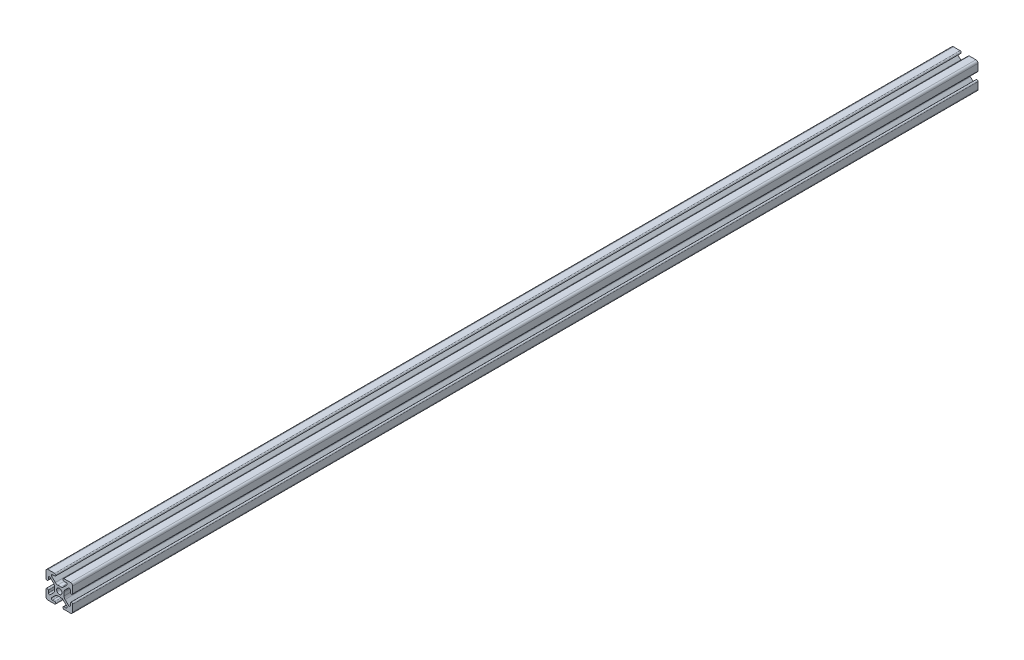
SolidWorks part; units mm, degrees
ref_plane "Front Plane" through (0, 0, 0) normal (0, 0, 1) x (1, 0, 0)
ref_plane "Top Plane" through (0, 0, 0) normal (0, 1, 0) x (1, 0, 0)
ref_plane "Right Plane" through (0, 0, 0) normal (1, 0, 0) x (0, 0, -1)
ref_plane "Plane1" through (0, 0, -25) normal (0, 0, -1) x (-1, 0, 0)
sketch "Sketch1" plane through (0, 0, -25) normal (0, 0, -1) x (-1, 0, 0)
  line L0 (12.5, 4.32) -> (12.5, 10.5371)
  line L1 (10.5371, 12.5) -> (4.32, 12.5)
  line L2 (4.32, 10.36) -> (6.42, 10.36)
  line L3 (7.1337, 8.6353) -> (3.7953, 5.3018)
  line L4 (1.5554, 4.375) -> (-1.5554, 4.375)
  line L5 (-3.7953, 5.3018) -> (-7.1337, 8.6353)
  line L6 (-6.42, 10.36) -> (-4.32, 10.36)
  line L7 (-4.32, 12.5) -> (-10.5371, 12.5)
  line L8 (-12.5, 10.5371) -> (-12.5, 4.32)
  line L9 (-10.36, 4.32) -> (-10.36, 6.3969)
  line L10 (-8.6363, 7.1116) -> (-5.4322, 3.9121)
  line L11 (-4.455, 1.5554) -> (-4.455, -1.5554)
  line L12 (-5.4322, -3.9121) -> (-8.6363, -7.1116)
  line L13 (-10.36, -6.3969) -> (-10.36, -4.32)
  line L14 (-12.5, -4.32) -> (-12.5, -10.5371)
  line L15 (-10.5371, -12.5) -> (-4.3879, -12.5)
  line L16 (-4.3879, -10.36) -> (-6.42, -10.36)
  line L17 (-7.1337, -8.6353) -> (-3.7953, -5.3018)
  line L18 (-1.5554, -4.375) -> (1.5554, -4.375)
  line L19 (3.7953, -5.3018) -> (7.1337, -8.6353)
  line L20 (6.42, -10.36) -> (4.3879, -10.36)
  line L21 (4.3879, -12.5) -> (10.5371, -12.5)
  line L22 (12.5, -10.5371) -> (12.5, -4.32)
  line L23 (10.36, -4.32) -> (10.36, -6.3969)
  line L24 (8.6363, -7.1116) -> (5.4322, -3.9121)
  line L25 (4.455, -1.5554) -> (4.455, 1.5554)
  line L26 (5.4322, 3.9121) -> (8.6363, 7.1116)
  line L27 (10.36, 6.3969) -> (10.36, 4.32)
  circle A0 centre (0, 0) radius 2.5
  arc A1 (12.5, 10.5371) -> (10.5371, 12.5) centre (10.5371, 10.5371) ccw
  arc A2 (4.32, 12.5) -> (4.32, 10.36) centre (4.32, 11.43) ccw
  arc A3 (6.42, 10.36) -> (7.1337, 8.6353) centre (6.42, 9.35) cw
  arc A4 (3.7953, 5.3018) -> (1.5554, 4.375) centre (1.5554, 7.545) cw
  arc A5 (-1.5554, 4.375) -> (-3.7953, 5.3018) centre (-1.5554, 7.545) cw
  arc A6 (-7.1337, 8.6353) -> (-6.42, 10.36) centre (-6.42, 9.35) cw
  arc A7 (-4.32, 10.36) -> (-4.32, 12.5) centre (-4.32, 11.43) ccw
  arc A8 (-10.5371, 12.5) -> (-12.5, 10.5371) centre (-10.5371, 10.5371) ccw
  arc A9 (-12.5, 4.32) -> (-10.36, 4.32) centre (-11.43, 4.32) ccw
  arc A10 (-10.36, 6.3969) -> (-8.6363, 7.1116) centre (-9.35, 6.3969) cw
  arc A11 (-5.4322, 3.9121) -> (-4.455, 1.5554) centre (-7.7855, 1.5554) cw
  arc A12 (-4.455, -1.5554) -> (-5.4322, -3.9121) centre (-7.7855, -1.5554) cw
  arc A13 (-8.6363, -7.1116) -> (-10.36, -6.3969) centre (-9.35, -6.3969) cw
  arc A14 (-10.36, -4.32) -> (-12.5, -4.32) centre (-11.43, -4.32) ccw
  arc A15 (-12.5, -10.5371) -> (-10.5371, -12.5) centre (-10.5371, -10.5371) ccw
  arc A16 (-4.3879, -12.5) -> (-4.3879, -10.36) centre (-4.3879, -11.43) ccw
  arc A17 (-6.42, -10.36) -> (-7.1337, -8.6353) centre (-6.42, -9.35) cw
  arc A18 (-3.7953, -5.3018) -> (-1.5554, -4.375) centre (-1.5554, -7.545) cw
  arc A19 (1.5554, -4.375) -> (3.7953, -5.3018) centre (1.5554, -7.545) cw
  arc A20 (7.1337, -8.6353) -> (6.42, -10.36) centre (6.42, -9.35) cw
  arc A21 (4.3879, -10.36) -> (4.3879, -12.5) centre (4.3879, -11.43) ccw
  arc A22 (10.5371, -12.5) -> (12.5, -10.5371) centre (10.5371, -10.5371) ccw
  arc A23 (12.5, -4.32) -> (10.36, -4.32) centre (11.43, -4.32) ccw
  arc A24 (10.36, -6.3969) -> (8.6363, -7.1116) centre (9.35, -6.3969) cw
  arc A25 (5.4322, -3.9121) -> (4.455, -1.5554) centre (7.7855, -1.5554) cw
  arc A26 (4.455, 1.5554) -> (5.4322, 3.9121) centre (7.7855, 1.5554) cw
  arc A27 (8.6363, 7.1116) -> (10.36, 6.3969) centre (9.35, 6.3969) cw
  arc A28 (10.36, 4.32) -> (12.5, 4.32) centre (11.43, 4.32) ccw
extrude "Boss-Extrude1" add sketch "Sketch1" against normal blind 850
